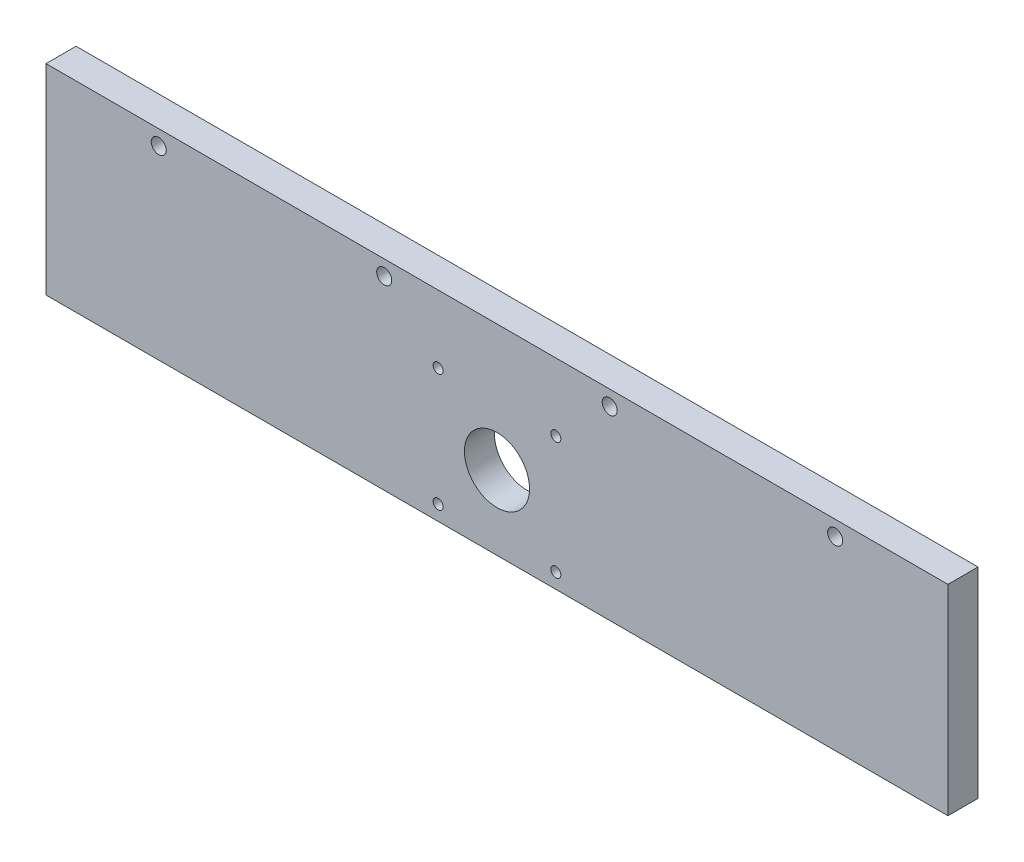
SolidWorks part; units mm, degrees
material "Beech"
ref_plane "Front Plane" through (0, 0, 0) normal (0, 0, 1) x (1, 0, 0)
ref_plane "Top Plane" through (0, 0, 0) normal (0, 1, 0) x (1, 0, 0)
ref_plane "Right Plane" through (0, 0, 0) normal (1, 0, 0) x (0, 0, -1)
sketch "Sketch1" plane through (0, 0, 0) normal (0, 0, 1) x (1, 0, 0)
  line L1 (-180, -40) -> (180, -40)
  line L2 (-180, -40) -> (-180, 40)
  line L3 (-180, 40) -> (180, 40)
  line L4 (180, -40) -> (180, 40)
  line L5 (-180, -40) -> (180, 40) construction
  line L6 (-180, 40) -> (180, -40) construction
  point P0 (0, 0)
extrude "Boss-Extrude1" add sketch "Sketch1" along normal blind 12
sketch "Sketch2" plane through (0, 0, 12) normal (0, 0, 1) x (1, 0, 0)
  line L0 (180, -40) -> (180, 40) construction
  line L1 (180, 40) -> (-180, 40) construction
  circle A0 centre (135, 34) radius 3
  dimension "D1" = 6
  dimension "D2" = 45
  dimension "D3" = 6
extrude "Cut-Extrude1" cut sketch "Sketch2" against normal up to next
pattern_linear "LPattern1" count 4 spacing 90 along (-1, 0, 0) of "Cut-Extrude1"
sketch "Sketch3" plane through (0, 0, 12) normal (0, 0, 1) x (1, 0, 0)
  line L0 (-180, -40) -> (180, -40) construction
  circle A0 centre (0, -10.5) radius 13
  dimension "D1" = 26
  dimension "D2" = 29.5
extrude "Cut-Extrude2" cut sketch "Sketch3" against normal up to next
sketch "Sketch4" plane through (0, 0, 12) normal (0, 0, 1) x (1, 0, 0)
  line L0 (0, 17.4189) -> (0, -17.4926) construction
  line L1 (-17.6695, 0) -> (16.7711, 0) construction
  circle A0 centre (-23.5, 13) radius 2
  circle A1 centre (0, -10.5) radius 13 construction
  circle A2 centre (-23.5, -34) radius 2
  dimension "D1" = 4
  dimension "D2" = 23.5
  dimension "D3" = 23.5
  dimension "D4" = 4
  dimension "D5" = 23.5
  dimension "D6" = 23.5
extrude "Cut-Extrude3" cut sketch "Sketch4" against normal up to next
mirror "Mirror2" about plane through (0, 0, 0) normal (1, 0, 0) of "Cut-Extrude3"
